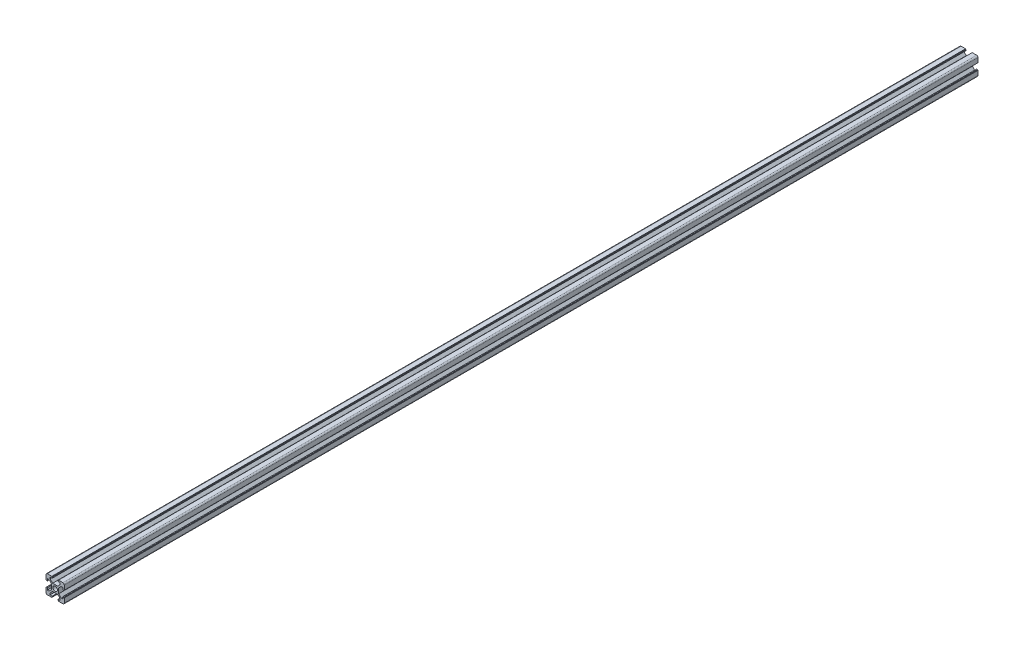
SolidWorks part; units mm, degrees
ref_plane "前视基准面" through (0, 0, 0) normal (0, 0, 1) x (1, 0, 0)
ref_plane "上视基准面" through (0, 0, 0) normal (0, 1, 0) x (1, 0, 0)
ref_plane "右视基准面" through (0, 0, 0) normal (1, 0, 0) x (0, 0, -1)
sketch "草图1" plane through (0, 0, 0) normal (0, 1, 0) x (1, 0, 0)
  line L4 (0, 500) -> (0, -500)
  point P1 (0, 0)
  dimension "D1" = 500
  dimension "D2" = 500
other "铝型材 20 X 20 X R1.5(1)"
ref_plane "基准面4" through (0, 0, -500) normal (0, 0, 1) x (1, 0, 0)
sketch "Sketch1" plane through (0, 0, -500) normal (0, 0, 1) x (1, 0, 0)
  line L0 (-3.6, 10) -> (-3.6, 9.5)
  line L1 (-3.6, 9.5) -> (-3.1, 9.5)
  line L2 (-3.1, 9.5) -> (-3.1, 8.5)
  line L3 (-3.1, 8.5) -> (-5.5, 8.5)
  line L4 (-8.5, -10) -> (-3.6, -10)
  line L5 (-10, -8.5) -> (-10, -3.6)
  line L6 (8.5, 10) -> (3.6, 10)
  line L7 (10, 8.5) -> (10, 3.6)
  line L8 (0, 14.8756) -> (0, 0) construction
  line L9 (0, 0) -> (14.1675, 0) construction
  line L10 (-5.5, 8.5) -> (-5.5, 6.65)
  line L11 (-5.5, 6.65) -> (-2.75, 3.9)
  line L12 (-2.75, 3.9) -> (2.75, 3.9)
  line L13 (5.5, 6.65) -> (2.75, 3.9)
  line L14 (5.5, 8.5) -> (5.5, 6.65)
  line L15 (3.1, 8.5) -> (5.5, 8.5)
  line L16 (3.1, 9.5) -> (3.1, 8.5)
  line L17 (3.6, 9.5) -> (3.1, 9.5)
  line L18 (3.6, 10) -> (3.6, 9.5)
  line L19 (-3.6, 10) -> (-8.5, 10)
  line L20 (10, 3.6) -> (9.5, 3.6)
  line L21 (9.5, 3.6) -> (9.5, 3.1)
  line L22 (9.5, 3.1) -> (8.5, 3.1)
  line L23 (8.5, 3.1) -> (8.5, 5.5)
  line L24 (8.5, 5.5) -> (6.65, 5.5)
  line L25 (6.65, 5.5) -> (3.9, 2.75)
  line L26 (3.9, 2.75) -> (3.9, -2.75)
  line L27 (6.65, -5.5) -> (3.9, -2.75)
  line L28 (8.5, -5.5) -> (6.65, -5.5)
  line L29 (8.5, -3.1) -> (8.5, -5.5)
  line L30 (9.5, -3.1) -> (8.5, -3.1)
  line L31 (9.5, -3.6) -> (9.5, -3.1)
  line L32 (10, -3.6) -> (9.5, -3.6)
  line L33 (3.6, -10) -> (3.6, -9.5)
  line L34 (3.6, -9.5) -> (3.1, -9.5)
  line L35 (3.1, -9.5) -> (3.1, -8.5)
  line L36 (3.1, -8.5) -> (5.5, -8.5)
  line L37 (5.5, -8.5) -> (5.5, -6.65)
  line L38 (5.5, -6.65) -> (2.75, -3.9)
  line L39 (2.75, -3.9) -> (-2.75, -3.9)
  line L40 (-5.5, -6.65) -> (-2.75, -3.9)
  line L41 (-5.5, -8.5) -> (-5.5, -6.65)
  line L42 (-3.1, -8.5) -> (-5.5, -8.5)
  line L43 (-3.1, -9.5) -> (-3.1, -8.5)
  line L44 (-3.6, -9.5) -> (-3.1, -9.5)
  line L45 (-3.6, -10) -> (-3.6, -9.5)
  line L46 (-10, -3.6) -> (-9.5, -3.6)
  line L47 (-9.5, -3.6) -> (-9.5, -3.1)
  line L48 (-9.5, -3.1) -> (-8.5, -3.1)
  line L49 (-8.5, -3.1) -> (-8.5, -5.5)
  line L50 (-8.5, -5.5) -> (-6.65, -5.5)
  line L51 (-6.65, -5.5) -> (-3.9, -2.75)
  line L52 (-3.9, -2.75) -> (-3.9, 2.75)
  line L53 (-6.65, 5.5) -> (-3.9, 2.75)
  line L54 (-8.5, 5.5) -> (-6.65, 5.5)
  line L55 (-8.5, 3.1) -> (-8.5, 5.5)
  line L56 (-9.5, 3.1) -> (-8.5, 3.1)
  line L57 (-9.5, 3.6) -> (-9.5, 3.1)
  line L58 (-10, 3.6) -> (-9.5, 3.6)
  line L59 (3.6, -10) -> (8.5, -10)
  line L60 (-10, 3.6) -> (-10, 8.5)
  line L61 (10, -3.6) -> (10, -8.5)
  circle A0 centre (0, 0) radius 2.5
  arc A1 (-10, 8.5) -> (-8.5, 10) centre (-8.5, 8.5) cw
  arc A2 (10, 8.5) -> (8.5, 10) centre (8.5, 8.5) ccw
  arc A3 (-8.5, -10) -> (-10, -8.5) centre (-8.5, -8.5) cw
  arc A4 (8.5, -10) -> (10, -8.5) centre (8.5, -8.5) ccw
  point P0 (-10, 0)
  point P1 (10, 0)
  point P2 (0, 10)
  point P3 (0, -10)
  point P4 (0, 0)
  point P5 (-10, -10)
  point P6 (10, -10)
  point P7 (10, 10)
  point P8 (-10, 10)
  point P13 (0, 0)
  point P36 (-10, 10)
  point P39 (10, 10)
  dimension "D1" = 11
  dimension "D2" = 20
  dimension "D3" = 6.2
  dimension "D4" = 7.2
  dimension "D5" = 6.1
  dimension "D6" = 5
  dimension "D7" = 1.5
  dimension "D8" = 45
  dimension "D9" = 0.5
  dimension "D10" = 1
  dimension "D11" = 5.5
